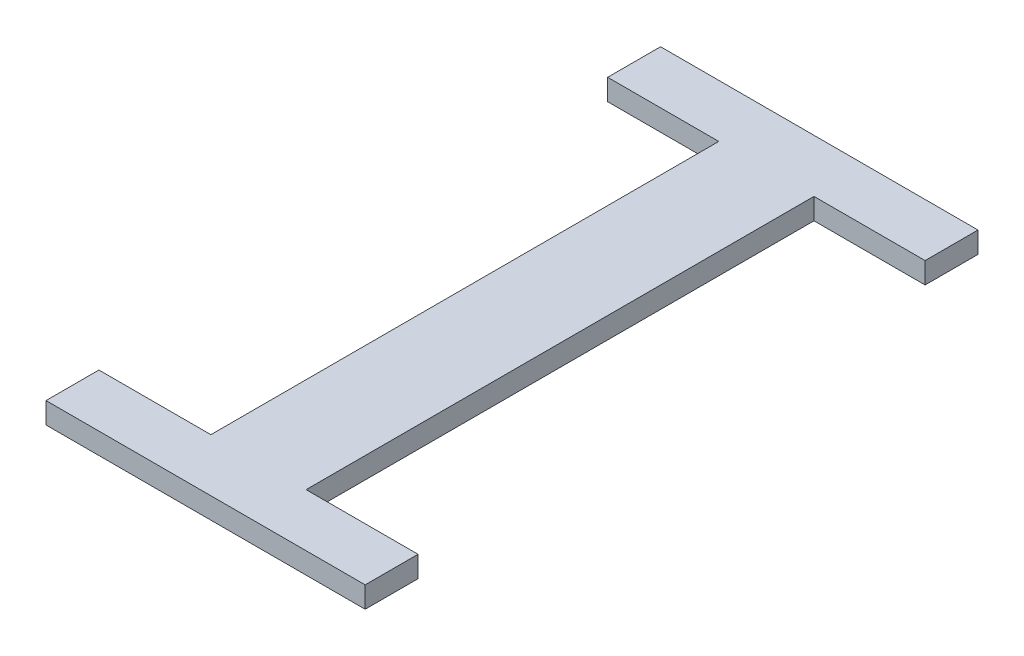
SolidWorks part; units mm, degrees
ref_plane "Front Plane" through (0, 0, 0) normal (0, 0, 1) x (1, 0, 0)
ref_plane "Top Plane" through (0, 0, 0) normal (0, 1, 0) x (1, 0, 0)
ref_plane "Right Plane" through (0, 0, 0) normal (1, 0, 0) x (0, 0, -1)
sketch "Sketch1" plane through (0, 0, 0) normal (0, 1, 0) x (1, 0, 0)
  line L1 (-155, 145) -> (155, 145)
  line L2 (-155, 145) -> (-155, -145)
  line L3 (-155, -145) -> (155, -145)
  line L4 (155, 145) -> (155, -145)
  line L5 (-155, 145) -> (155, -145) construction
  line L6 (-155, -145) -> (155, 145) construction
  point P0 (0, 0)
  dimension "D1" = 310
  dimension "D2" = 290
extrude "Boss-Extrude1" add sketch "Sketch1" along normal blind 10
sketch "Sketch2" plane through (0, 10, 0) normal (0, 1, 0) x (1, 0, 0)
  line L0 (-85, 145) -> (-115, 87.5)
  line L1 (155, 145) -> (-155, 145) construction
  line L2 (-115, 87.5) -> (-115, -87.5)
  line L5 (-115, -87.5) -> (-85, -145)
  line L6 (-155, -145) -> (155, -145) construction
  line L7 (-85, -145) -> (-155, -145)
  line L8 (-155, -145) -> (-155, 145)
  line L9 (-155, 145) -> (-85, 145)
  line L10 (0, -187.825) -> (0, 187.825) construction
  line L11 (155, -145) -> (155, 145)
  line L12 (85, -145) -> (155, -145)
  line L13 (115, -87.5) -> (85, -145)
  line L14 (115, 87.5) -> (115, -87.5)
  line L15 (85, 145) -> (115, 87.5)
  line L16 (155, 145) -> (85, 145)
  dimension "D1" = 70
  dimension "D2" = 175
  dimension "D3" = 40
extrude "Cut-Extrude1" cut sketch "Sketch2" against normal through all
sketch "Sketch3" plane through (0, 0, 0) normal (0, -1, 0) x (1, 0, 0)
  line L0 (-75, -145) -> (-75, -120)
  line L1 (85, -145) -> (-85, -145) construction
  line L2 (-75, -120) -> (-22.5, -120)
  line L4 (-85, 145) -> (85, 145) construction
  line L6 (-85, 145) -> (-115, 87.5)
  line L7 (-115, 87.5) -> (-115, -87.5)
  line L8 (-115, -87.5) -> (-85, -145)
  line L9 (-85, -145) -> (-75, -145)
  line L10 (-85, 145) -> (-75.408, 145)
  line L11 (-75.408, 145) -> (-75.408, 120)
  line L12 (-75.408, 120) -> (-22.5, 120)
  line L13 (-22.5, -120) -> (-22.5, 120)
  line L14 (0, -5.5) -> (0, 5.5) construction
  line L15 (75, -120) -> (22.5, -120)
  line L16 (75, -145) -> (75, -120)
  line L17 (85, -145) -> (75, -145)
  line L18 (115, -87.5) -> (85, -145)
  line L19 (115, 87.5) -> (115, -87.5)
  line L20 (85, 145) -> (75.408, 145)
  line L21 (85, 145) -> (115, 87.5)
  line L22 (75.408, 145) -> (75.408, 120)
  line L23 (75.408, 120) -> (22.5, 120)
  line L24 (22.5, -120) -> (22.5, 120)
  dimension "D1" = 240
  dimension "D2" = 10
  dimension "D3" = 52.5
extrude "Cut-Extrude2" cut sketch "Sketch3" against normal through all
